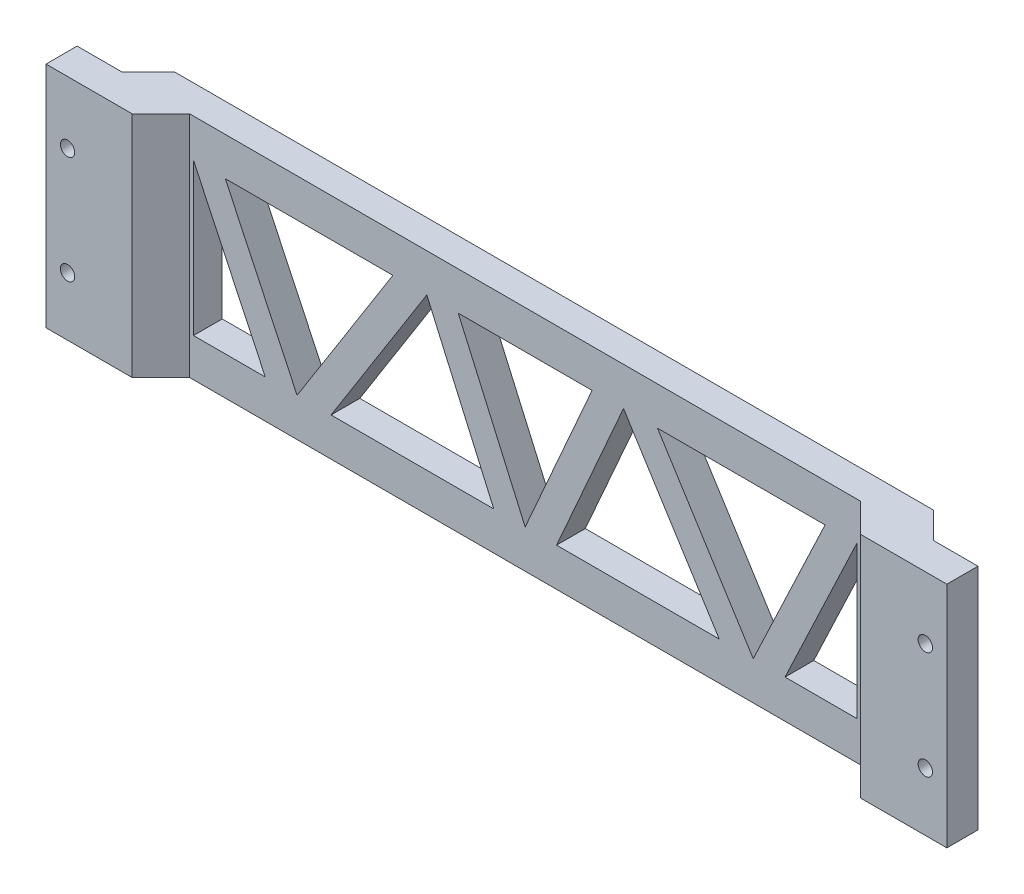
SolidWorks part; units mm, degrees
ref_plane "前视基准面" through (0, 0, 0) normal (0, 0, 1) x (1, 0, 0)
ref_plane "上视基准面" through (0, 0, 0) normal (0, 1, 0) x (1, 0, 0)
ref_plane "右视基准面" through (0, 0, 0) normal (1, 0, 0) x (0, 0, -1)
sketch "草图1" plane through (0, 0, 0) normal (0, 1, 0) x (1, 0, 0)
  line L1 (70.07, 0) -> (76.07, -6)
  line L2 (76.07, -6) -> (94.07, -6)
  line L8 (0, 25.0732) -> (0, -24.5324) construction
  line L12 (79.27, 6) -> (0, 6)
  line L13 (70.07, 0) -> (-70.07, 0)
  line L17 (-79.27, 6) -> (0, 6)
  line L19 (-76.07, -6) -> (-94.07, -6)
  line L20 (-70.07, 0) -> (-76.07, -6)
  line L21 (-79.27, 6) -> (-84.77, 0.5)
  line L22 (-84.77, 0.5) -> (-94.07, 0.5)
  line L23 (-94.07, 0.5) -> (-94.07, -6)
  line L24 (79.27, 6) -> (84.77, 0.5)
  line L25 (84.77, 0.5) -> (94.07, 0.5)
  line L26 (94.07, 0.5) -> (94.07, -6)
  point P3 (0, 0)
  point P8 (39.635, 6)
  point P12 (39.635, 6)
  point P15 (-39.635, 6)
  dimension "D1" = 18
  dimension "D2" = 6
  dimension "D3" = 45
  dimension "D4" = 6
  dimension "D5" = 188.14
  dimension "D6" = 9.3
  dimension "D7" = 9.3
  dimension "D8" = 6.5
extrude "凸台-拉伸1" add sketch "草图1" along normal blind 47.7
ref_plane "基准面1" through (0, 0, -6) normal (0, 0, -1) x (-1, 0, 0)
sketch "草图2" plane through (0, 0, -6) normal (0, 0, -1) x (-1, 0, 0)
  line L18 (79.27, 8) -> (-79.27, 8)
  line L19 (79.27, 47.7) -> (-79.27, 47.7)
  line L20 (79.27, 0) -> (-79.27, 0)
  line L21 (69.27, 47.7) -> (69.27, 0)
  line L22 (-69.27, 47.7) -> (-69.27, 0)
  line L23 (-79.27, 39.7) -> (79.27, 39.7)
  line L24 (-79.27, 47.7) -> (-79.27, 0) construction
  line L25 (79.27, 47.7) -> (79.27, 0) construction
  line L26 (0, 0) -> (0, 47.7) construction
  line L27 (-33.245, 39.7) -> (-33.245, 8) construction
  line L28 (-69.27, 39.7) -> (-54.27, 8)
  line L29 (-62.6322, 39.7) -> (-47.6322, 8)
  line L30 (-47.6322, 8) -> (-27.6322, 39.7)
  line L31 (-40.5378, 8) -> (-20.5378, 39.7)
  line L32 (-20.5378, 39.7) -> (-6.5576, 8)
  line L33 (-13.9802, 39.7) -> (0, 8)
  line L34 (62.6322, 39.7) -> (47.6322, 8)
  line L35 (13.9802, 39.7) -> (0, 8)
  line L36 (20.5378, 39.7) -> (6.5576, 8)
  line L37 (40.5378, 8) -> (20.5378, 39.7)
  line L38 (47.6322, 8) -> (27.6322, 39.7)
  line L39 (69.27, 39.7) -> (54.27, 8)
  dimension "D1" = 10
  dimension "D2" = 10
  dimension "D3" = 8
  dimension "D4" = 8
  dimension "D5" = 36.025
  dimension "D6" = 6
  dimension "D7" = 6
  dimension "D8" = 6
  dimension "D9" = 15
  dimension "D10" = 20
extrude "切除-拉伸1" cut sketch "草图2" against normal blind 10 contours L28 L22 L18 | L29 L30 L23 | L32 L31 L18 | L35 L23 L33 | L18 L37 L36 | L38 L34 L23 | L21 L39 L18
sketch "草图4" plane through (0, 0, -0.5) normal (0, 0, -1) x (-1, 0, 0)
  line L1 (-94.07, 47.7) -> (-94.07, 0) construction
  line L3 (-94.07, 47.7) -> (-84.77, 47.7) construction
  line L4 (94.07, 47.7) -> (94.07, 0) construction
  line L6 (84.77, 47.7) -> (94.07, 47.7) construction
  circle A0 centre (-89.57, 34.7) radius 1.5
  circle A1 centre (-89.57, 12.2) radius 1.5
  circle A2 centre (89.57, 34.7) radius 1.5
  circle A3 centre (89.57, 12.2) radius 1.5
  dimension "D1" = 4.5
  dimension "D4" = 4.5
  dimension "D2" = 22.5
  dimension "D3" = 13
  dimension "D5" = 13
  dimension "D6" = 22.5
  dimension "D7" = 4.5
  dimension "D8" = 4.5
extrude "切除-拉伸2" cut sketch "草图4" against normal blind 10
sketch "草图6" plane through (0, 0, -0.5) normal (0, 0, -1) x (-1, 0, 0)
  circle A0 centre (-89.57, 34.7) radius 2.5
  circle A1 centre (-89.57, 12.2) radius 2.5
  circle A2 centre (89.57, 34.7) radius 2.5
  circle A3 centre (89.57, 12.2) radius 2.5
extrude "切除-拉伸4" cut sketch "草图6" against normal blind 3
